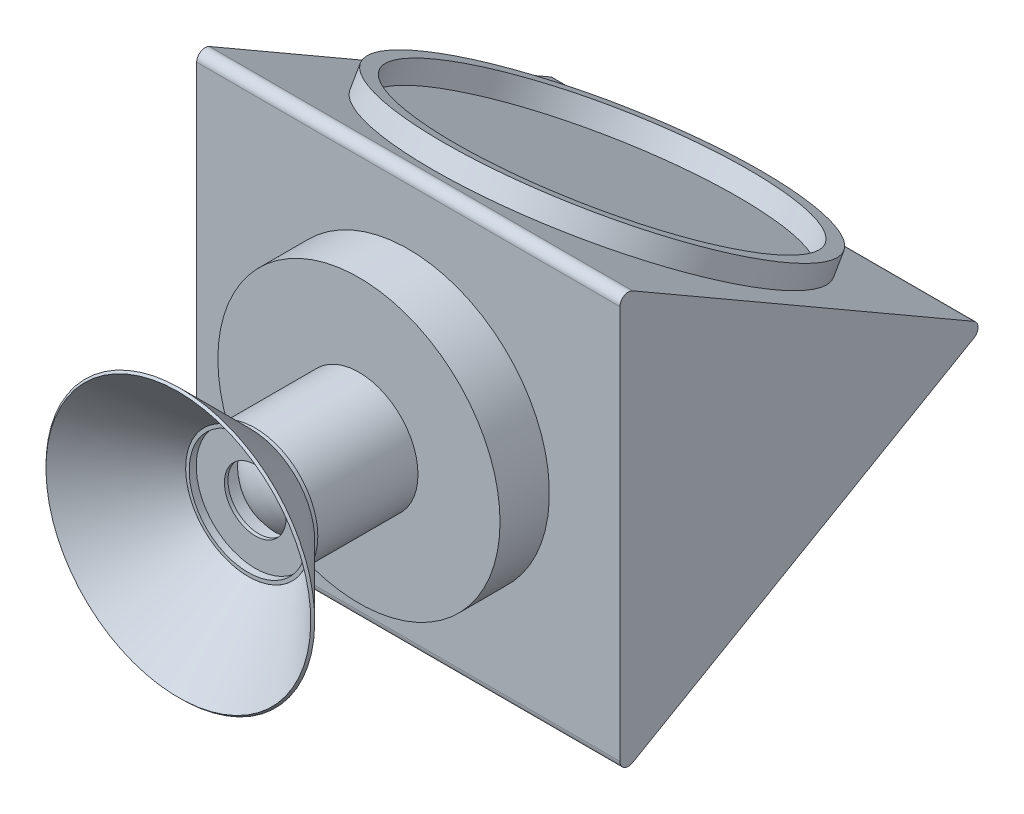
SolidWorks part; units mm, degrees
material "6061 Alloy"
ref_plane "Front Plane" through (0, 0, 0) normal (0, 0, 1) x (1, 0, 0)
ref_plane "Top Plane" through (0, 0, 0) normal (0, 1, 0) x (1, 0, 0)
ref_plane "Right Plane" through (0, 0, 0) normal (1, 0, 0) x (0, 0, -1)
sketch "Sketch3" plane through (0, 0, 0) normal (1, 0, 0) x (0, 0, -1)
  line L0 (0, 0) -> (0, 1500)
  line L1 (0, 1500) -> (1299.0381, 750) construction
  line L2 (0, 0) -> (1299.0381, 750) construction
  line L3 (0, 1500) -> (1299.0381, 750)
  line L4 (1299.0381, 750) -> (0, 0)
  dimension "D1" = 1500
  dimension "D2" = 60
  dimension "D3" = 60
  dimension "D4" = 1500
  dimension "D5" = 1500
extrude "Boss-Extrude1" add sketch "Sketch3" along normal blind 1500
fillet "Fillet5" radius 30 1 edges at (750, 1500, 0)
fillet "Fillet6" radius 30 2 edges at (750, 0, 0) (750, 750, -1299.0381)
sketch "Sketch5" plane through (0, 0, 0) normal (0, 0, 1) x (1, 0, 0)
  line L0 (750, 1448.0385) -> (750, 51.9615) construction
  line L1 (1500, 1448.0385) -> (0, 1448.0385) construction
  line L2 (0, 51.9615) -> (1500, 51.9615) construction
  circle A0 centre (750, 750) radius 500
  dimension "D1" = 1000
extrude "Boss-Extrude2" add sketch "Sketch5" along normal blind 175
ref_plane "Plane1" through (0, 750, 0) normal (0, 1, 0) x (1, 0, 0)
ref_plane "Plane2" through (750, 0, 0) normal (1, 0, 0) x (0, 0, -1)
sketch "Sketch8" plane through (750, 0, 0) normal (1, 0, 0) x (0, 0, -1)
  line L0 (1269.0381, 750) -> (-1196.9603, 750) construction
  line L1 (825, 750) -> (-825, 750) construction
  arc A0 (1254.0381, 724.0192) -> (1254.0381, 775.9808) centre (1239.0381, 750) ccw construction
sketch "Sketch9" plane through (750, 0, 0) normal (1, 0, 0) x (0, 0, -1)
  line L0 (-175, 919.7224) -> (-425, 919.7224)
  line L1 (-175, 1250) -> (-175, 250) construction
  line L2 (-175, 919.7224) -> (-175, 750)
  line L3 (-175, 750) -> (-525, 750)
  line L4 (1269.0381, 750) -> (-1196.9603, 750) construction
  arc A0 (-525, 750) -> (-425, 919.7224) centre (-330.9715, 750) cw
  dimension "D1" = 350
  dimension "D2" = 250
revolve "Revolve1" add sketch "Sketch9" angle 360 about L3
sketch "Sketch10" plane through (0, 0, 175) normal (0, 0, 1) x (1, 0, 0)
  circle A0 centre (750, 750) radius 199.2459
extrude "Extrude-Thin2" add sketch "Sketch10" along normal blind 355 thin
sketch "Sketch11" plane through (0, 0, 530) normal (0, 0, 1) x (1, 0, 0)
  circle A0 centre (750, 750) radius 209.2459
  circle A2 centre (750, 750) radius 109.2459
  dimension "D2" = 100
extrude "Boss-Extrude3" add sketch "Sketch11" along normal blind 12.5
sketch "Sketch12" plane through (0, 0, 542.5) normal (0, 0, 1) x (1, 0, 0)
  circle A0 centre (750, 750) radius 209.2459
  circle A1 centre (750, 750) radius 221.7459
  dimension "D1" = 12.5
extrude "Boss-Extrude5" add sketch "Sketch12" along normal blind 25 separate body
sketch "Sketch13" plane through (750, 0, 0) normal (1, 0, 0) x (0, 0, -1)
  line L0 (-567.5, 971.7459) -> (-814.9874, 1219.2333)
  line L1 (1269.0381, 750) -> (-1196.9603, 750) construction
  dimension "D1" = 350
  dimension "D2" = 45
revolve "Revolve-Thin1" add sketch "Sketch13" angle 360 about L0
sketch "Sketch15" plane through (0, 1125, -649.5191) normal (0, 0.866, -0.5) x (1, 0, 0)
  line L0 (750, -800.8423) -> (750, 800.8423) construction
  circle A0 centre (750, 0) radius 600
  circle A1 centre (750, 0) radius 650
  dimension "D1" = 1200
  dimension "D2" = 50
extrude "Boss-Extrude6" add sketch "Sketch15" along normal blind 75
